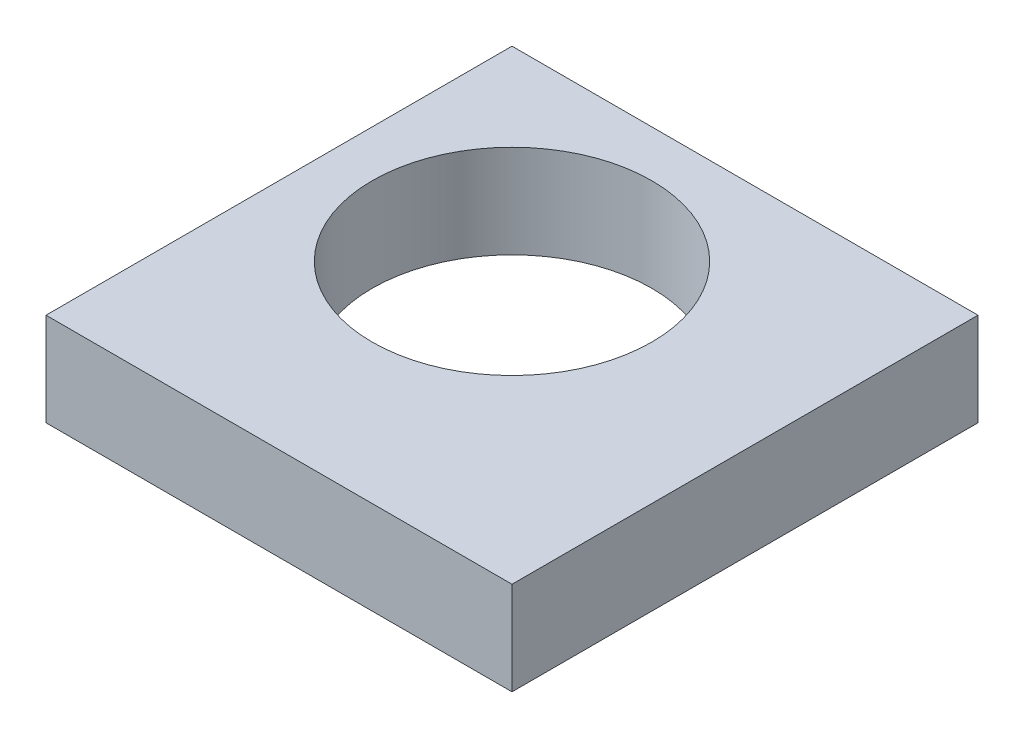
SolidWorks part; units mm, degrees
ref_plane "Front Plane" through (0, 0, 0) normal (0, 0, 1) x (1, 0, 0)
ref_plane "Top Plane" through (0, 0, 0) normal (0, 1, 0) x (1, 0, 0)
ref_plane "Right Plane" through (0, 0, 0) normal (1, 0, 0) x (0, 0, -1)
sketch "Sketch1" plane through (0, 0, 0) normal (0, 1, 0) x (1, 0, 0)
  line L1 (25, 25) -> (-25, 25)
  line L2 (25, 25) -> (25, -25)
  line L3 (25, -25) -> (-25, -25)
  line L4 (-25, 25) -> (-25, -25)
  line L5 (25, 25) -> (-25, -25) construction
  line L6 (25, -25) -> (-25, 25) construction
  point P0 (0, 0)
  dimension "D1" = 50
  dimension "D2" = 50
extrude "Boss-Extrude1" add sketch "Sketch1" along normal blind 10
sketch "Sketch3" plane through (0, 10, 0) normal (0, 1, 0) x (1, 0, 0)
  circle A0 centre (-5, 5) radius 15
  dimension "D1" = 5
  dimension "D3" = 30
  dimension "D2" = 5
extrude "Cut-Extrude1" cut sketch "Sketch3" against normal blind 10
